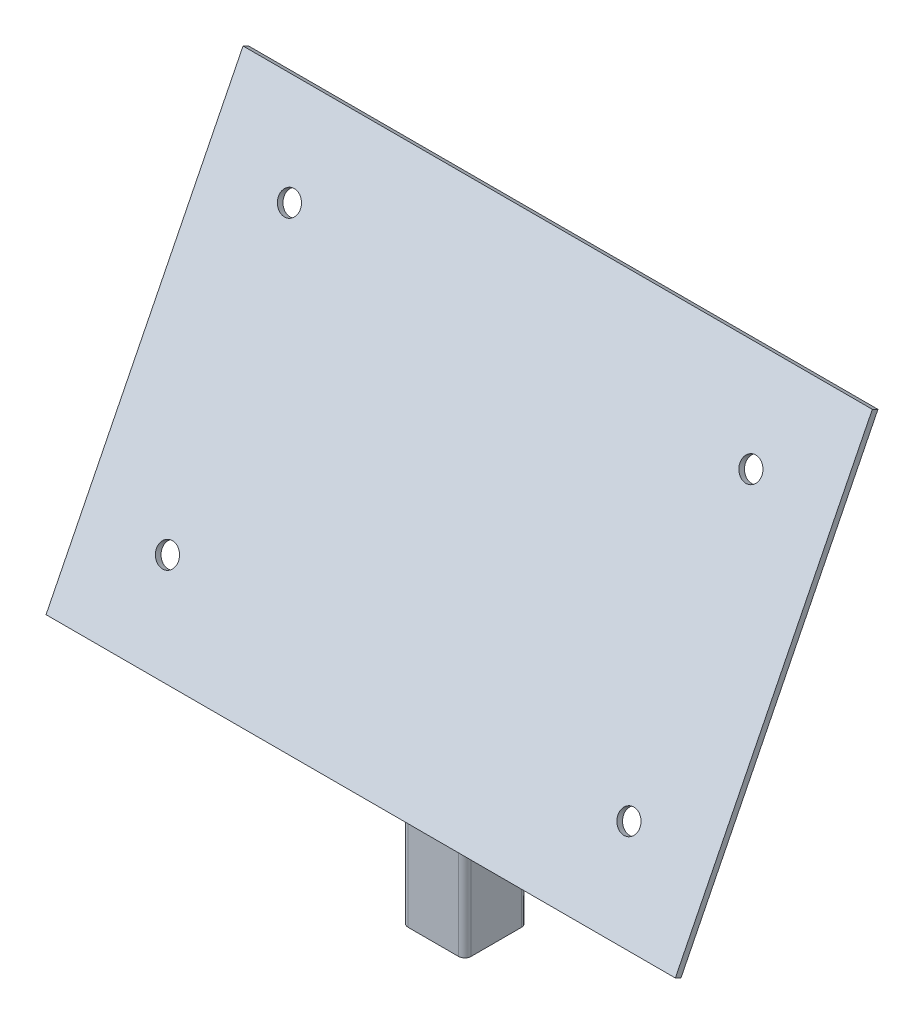
SolidWorks part; units mm, degrees
ref_plane "Plan de face" through (0, 0, 0) normal (0, 0, 1) x (1, 0, 0)
ref_plane "Plan de dessus" through (0, 0, 0) normal (0, 1, 0) x (1, 0, 0)
ref_plane "Plan de droite" through (0, 0, 0) normal (1, 0, 0) x (0, 0, -1)
sketch "Esquisse1" plane through (0, 0, 0) normal (0, 1, 0) x (1, 0, 0)
  line L1 (-12, -15) -> (12, -15)
  line L2 (-15, -12) -> (-15, 12)
  line L3 (-12, 15) -> (12, 15)
  line L4 (15, -12) -> (15, 12)
  line L5 (0, 15) -> (0, -15) construction
  line L6 (-15, 0) -> (15, 0) construction
  line L7 (-10, -13) -> (10, -13)
  line L8 (-13, -10) -> (-13, 10)
  line L9 (-10, 13) -> (10, 13)
  line L10 (13, -10) -> (13, 10)
  line L11 (0, 13) -> (0, -13) construction
  line L12 (-13, 0) -> (13, 0) construction
  arc A0 (10, -13) -> (13, -10) centre (10, -10) ccw
  arc A1 (-13, 10) -> (-10, 13) centre (-10, 10) cw
  arc A2 (12, -15) -> (15, -12) centre (12, -12) ccw
  arc A3 (-10, -13) -> (-13, -10) centre (-10, -10) cw
  arc A4 (10, 13) -> (13, 10) centre (10, 10) cw
  arc A5 (-15, 12) -> (-12, 15) centre (-12, 12) cw
  arc A6 (-12, -15) -> (-15, -12) centre (-12, -12) cw
  arc A7 (12, 15) -> (15, 12) centre (12, 12) cw
  point P0 (0, 0)
  point P5 (0, 0)
  point P13 (13, -13)
  point P19 (-13, 13)
  point P24 (-13, -13)
  point P29 (-15, 15)
  point P32 (-15, -15)
  point P35 (15, 15)
  dimension "D5" = 3
  dimension "D1" = 30
  dimension "D2" = 30
  dimension "D3" = 26
  dimension "D4" = 26
extrude "Boss.-Extru.1" add sketch "Esquisse1" along normal blind 200
sketch "Esquisse2" plane through (15, 0, 0) normal (1, 0, 0) x (0, 0, -1)
  line L0 (15, 200) -> (-15, 140)
  line L1 (-15, 200) -> (-15, 0) construction
  line L2 (-15, 140) -> (-15, 200)
  line L3 (-15, 200) -> (15, 200)
  dimension "D1" = 60
extrude "Enlèv. mat.-Extru.1" cut sketch "Esquisse2" against normal blind 100
ref_plane "Plan2" through (0, 34, 68) normal (0, 0.4472, 0.8944) x (1, 0, 0)
sketch "Esquisse3" plane through (0, 34, 68) normal (0, 0.4472, 0.8944) x (1, 0, 0)
  line L0 (-13, 129.6919) -> (-13, 174.4133) construction
  line L1 (-150, 47.0526) -> (150, 47.0526)
  line L2 (-150, 47.0526) -> (-150, 257.0526)
  line L3 (-150, 257.0526) -> (150, 257.0526)
  line L4 (150, 47.0526) -> (150, 257.0526)
  line L5 (0, 257.0526) -> (0, 47.0526) construction
  line L6 (-150, 152.0526) -> (150, 152.0526) construction
  line L10 (-10, 181.1215) -> (10, 181.1215) construction
  point P0 (0, 152.0526)
  point P6 (-13, 152.0526)
  point P12 (0, 0)
  point P15 (0, 181.1215)
  dimension "D1" = 300
  dimension "D2" = 210
extrude "Boss.-Extru.2" add sketch "Esquisse3" along normal blind 3
sketch "Esquisse4" plane through (0, 34, 68) normal (0, 0.4472, 0.8944) x (1, 0, 0)
  line L0 (150, 257.0526) -> (-150, 257.0526) construction
  line L1 (-150, 257.0526) -> (-150, 47.0526) construction
  line L2 (-150, 47.0526) -> (150, 47.0526) construction
  line L3 (150, 47.0526) -> (150, 257.0526) construction
  circle A0 centre (-110, 217.0526) radius 5.25
  circle A1 centre (110, 217.0526) radius 5.25
  circle A2 centre (110, 87.0526) radius 5.25
  circle A3 centre (-110, 87.0526) radius 5.25
  point P14 (0, 0)
  dimension "D1" = 10.5
  dimension "D2" = 40
  dimension "D3" = 40
  dimension "D4" = 40
  dimension "D5" = 40
  dimension "D6" = 40
  dimension "D7" = 40
  dimension "D8" = 40
extrude "Enlèv. mat.-Extru.2" cut sketch "Esquisse4" along normal through all both and the other way through all
